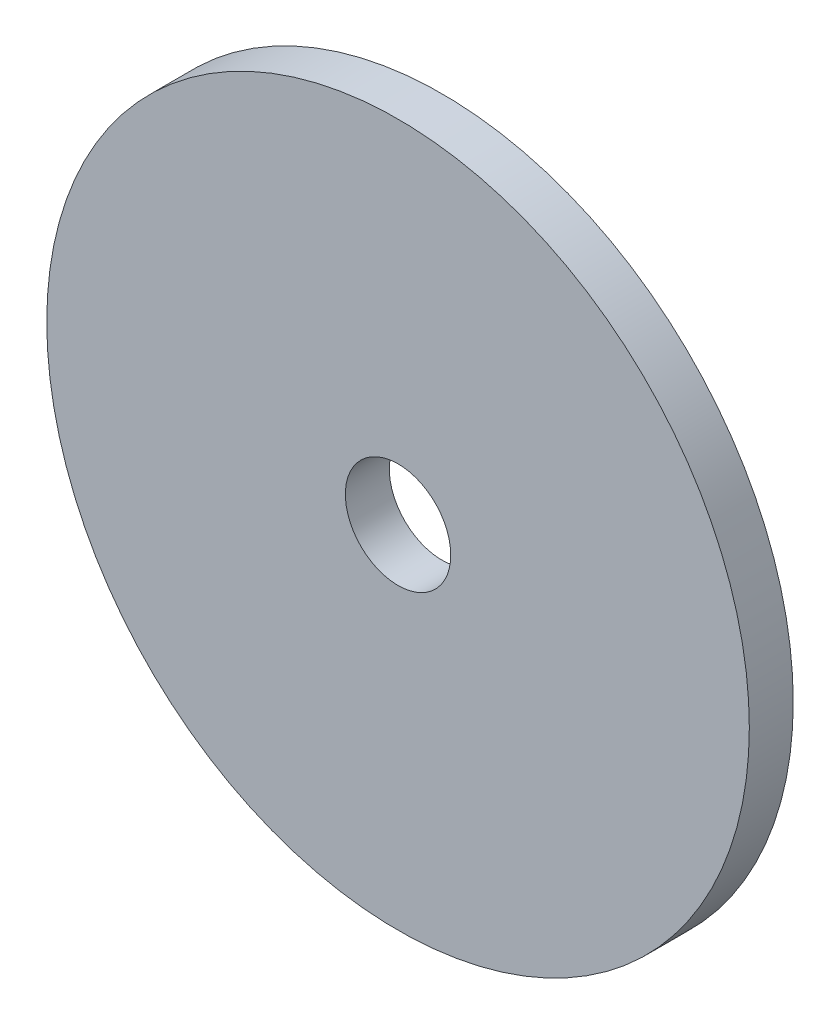
SolidWorks part; units mm, degrees
ref_plane "Front Plane" through (0, 0, 0) normal (0, 0, 1) x (1, 0, 0)
ref_plane "Top Plane" through (0, 0, 0) normal (0, 1, 0) x (1, 0, 0)
ref_plane "Right Plane" through (0, 0, 0) normal (1, 0, 0) x (0, 0, -1)
sketch "Sketch1" plane through (0, 0, 0) normal (0, 0, 1) x (1, 0, 0)
  circle A0 centre (0, 0) radius 80
  circle A1 centre (0, 0) radius 12 construction
  circle A2 centre (0, 0) radius 12
  dimension "D1" = 160
extrude "Boss-Extrude1" add sketch "Sketch1" along normal blind 5
sketch "Sketch2" plane through (0, 0, 5) normal (0, 0, 1) x (1, 0, 0)
  circle A0 centre (0, 0) radius 12 construction
  circle A1 centre (0, 0) radius 12
  circle A4 centre (0, 0) radius 14.5
  circle A5 centre (0, 0) radius 14.5
  dimension "D1" = 2.5
extrude "Boss-Extrude2" add sketch "Sketch2" against normal blind 10
sketch "Sketch3" plane through (0, 0, 5) normal (0, 0, 1) x (1, 0, 0)
  circle A1 centre (0, 0) radius 80
  circle A2 centre (0, 0) radius 80
  circle A3 centre (0, 0) radius 79
  dimension "D1" = 0
  dimension "D2" = 1
extrude "Boss-Extrude3" add sketch "Sketch3" against normal blind 10
